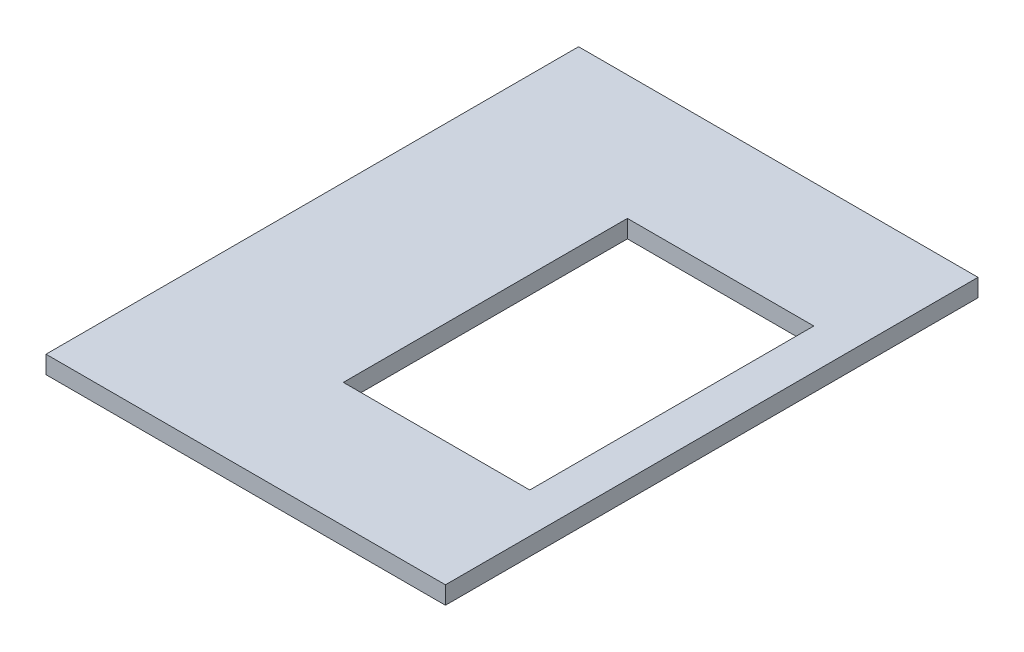
SolidWorks part; units mm, degrees
ref_plane "Ön Düzlem" through (0, 0, 0) normal (0, 0, 1) x (1, 0, 0)
ref_plane "Üst Düzlem" through (0, 0, 0) normal (0, 1, 0) x (1, 0, 0)
ref_plane "Sağ Düzlem" through (0, 0, 0) normal (1, 0, 0) x (0, 0, -1)
sketch "Çizim1" plane through (0, 0, 0) normal (0, 1, 0) x (1, 0, 0)
  line L1 (-22.5, -30) -> (22.5, -30)
  line L2 (-22.5, -30) -> (-22.5, 30)
  line L3 (-22.5, 30) -> (22.5, 30)
  line L4 (22.5, -30) -> (22.5, 30)
  line L5 (-22.5, -30) -> (22.5, 30) construction
  line L6 (-22.5, 30) -> (22.5, -30) construction
  point P0 (0, 0)
extrude "Yükseklik-Ekstrüzyon1" add sketch "Çizim1" along normal blind 2
sketch "Çizim2" plane through (0, 2, 0) normal (0, 1, 0) x (1, 0, 0)
  line L6 (-3, 16) -> (18, 16)
  line L7 (-3, 16) -> (-3, -16)
  line L8 (-3, -16) -> (18, -16)
  line L9 (18, 16) -> (18, -16)
  line L10 (-3, 16) -> (18, -16) construction
  line L11 (-3, -16) -> (18, 16) construction
  point P10 (7.5, 0)
  dimension "D2" = 32
  dimension "D3" = 21
extrude "Kes-Ekstrüzyon1" cut sketch "Çizim2" against normal blind 2
